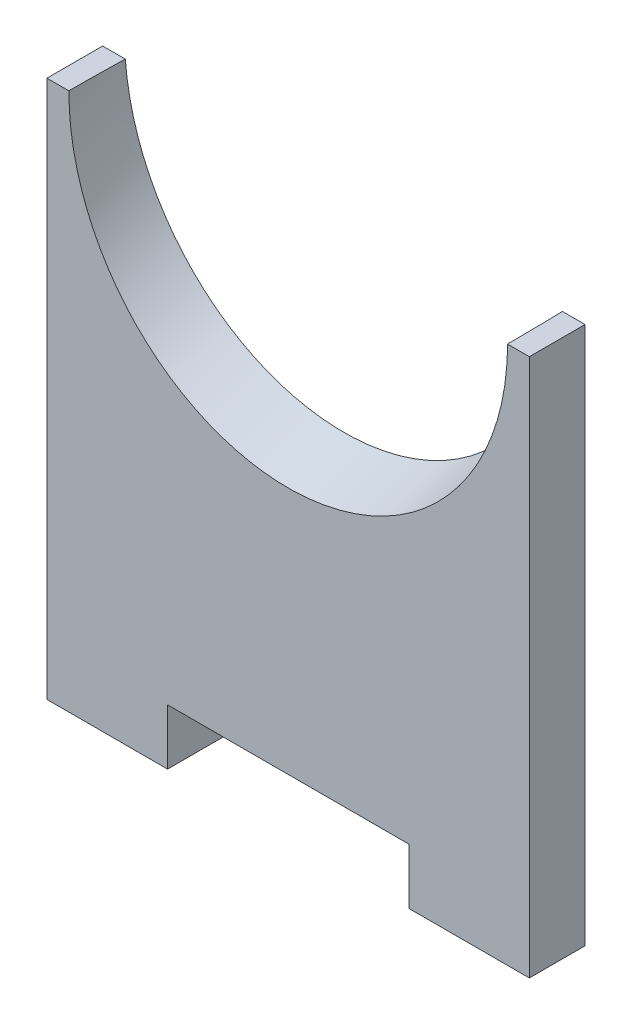
SolidWorks part; units mm, degrees
ref_plane "Front Plane" through (0, 0, 0) normal (0, 0, 1) x (1, 0, 0)
ref_plane "Top Plane" through (0, 0, 0) normal (0, 1, 0) x (1, 0, 0)
ref_plane "Right Plane" through (0, 0, 0) normal (1, 0, 0) x (0, 0, -1)
sketch "Sketch2" plane through (0, 0, 0) normal (0, 0, 1) x (1, 0, 0)
  line L0 (27.5, 55) -> (27.5, 29.1207) construction
  line L1 (13.75, 0) -> (41.25, 0)
  line L2 (0, 0) -> (0, 55)
  line L3 (0, 55) -> (55, 55)
  line L4 (55, 0) -> (55, 55)
  line L6 (0, 0) -> (0, -6.35)
  line L7 (0, -6.35) -> (13.75, -6.35)
  line L8 (13.75, 0) -> (13.75, -6.35)
  line L9 (55, -6.35) -> (41.25, -6.35)
  line L10 (41.25, 0) -> (41.25, -6.35)
  line L12 (55, 0) -> (55, -6.35)
  dimension "D1" = 55
  dimension "D2" = 55
  dimension "D3" = 13.75
  dimension "D4" = 6.35
  dimension "D5" = 6.35
extrude "Boss-Extrude1" add sketch "Sketch2" along normal blind 6.35
ref_plane "Plane1" through (27.5, 0, 0) normal (1, 0, 0) x (0, 0, -1)
sketch "Sketch5" plane through (27.5, 0, 0) normal (1, 0, 0) x (0, 0, -1)
  line L0 (-6.35, 50) -> (-0.2019, 50) construction
  line L1 (-6.35, 50) -> (0, 52.3112)
  line L2 (-6.35, -6.35) -> (-6.35, 55) construction
  line L3 (0, -6.35) -> (0, 55) construction
  dimension "D1" = 50
  dimension "D2" = 20
sketch "Sketch8" plane through (27.5, 0, 0) normal (1, 0, 0) x (0, 0, -1)
  line L0 (0, 57.2032) -> (-6.35, 54.892) construction
  line L1 (0, 55) -> (0, -6.35) construction
  line L2 (-6.35, 55) -> (-6.35, -6.35) construction
  line L3 (-6.35, 54.892) -> (4.3745, 54.892) construction
  line L4 (-6.35, 54.892) -> (-1.6436, 41.9611) construction
  line L5 (-6.35, 54.892) -> (-9.6815, 64.0451) construction
  dimension "D2" = 20
  dimension "D1" = 54.892
  dimension "D4" = 90
  dimension "D3" = 90
sketch "Sketch9" plane through (0, 0, 0) normal (-1, 0, 0) x (0, 0, 1)
  line L0 (6.35, 54.892) -> (0, 57.2032) construction
  line L1 (6.35, 54.892) -> (0, 54.892) construction
  line L2 (6.35, 54.892) -> (-4.3745, 54.892) construction
  line L3 (0, 55) -> (0, -6.35) construction
  line L4 (6.35, 54.892) -> (0, 37.4455) construction
  line L5 (6.35, 54.892) -> (1.6436, 41.9611) construction
  line L6 (6.35, 54.892) -> (5.4251, 52.3508) construction
  line L7 (6.35, 54.892) -> (9.6815, 64.0451) construction
ref_plane "Plane3" through (0, 4.3803, -12.0348) normal (0, -0.342, 0.9397) x (1, 0, 0)
sketch "Sketch10" plane through (0, 4.3803, -12.0348) normal (0, -0.342, 0.9397) x (1, 0, 0)
  circle A0 centre (27.5, 53.7534) radius 25
  dimension "D1" = 50
extrude "Cut-Extrude1" cut sketch "Sketch10" against normal through all both and the other way through all
equation "\"Wheel Thickness\"= 1in"
equation "\"Wheel Diameter\"= 3in"
equation "\"Motor Rear Diameter\" = 36.2mm"
equation "\"Motor Front Diameter\" = 12mm"
equation "\"Material Thickness\" = .25in"
equation "\"Wheel Cutout Diameter\"= 2cm"
equation "\"Motor Mount Tab Thickness\" = 100mm"
equation "\"Motor Mount Tab Height\" = 40mm"
equation "\"Motor Shaft Diameter\" = 3mm"
equation "\"Wheel Radius Clearance\" = 5mm"
equation "\"Wheel Cutout Width\" = 1.5in"
equation "\"Base Diameter\" = 10in"
equation "\"Wheel Mount Distance\" = 5mm"
equation "\"Motor Mount Distance\" = 50mm"
equation "\"Motor Cutout Length\" = 6in"
equation "\"Motor Cutout Height\" = 2in "
equation "\"Rod Diameter\" = 3/8in"
equation "\"Rod Length\" = 1.5in"
equation "\"Barrel Front Length\" = 1.8in"
equation "\"Barrerl Rear Length\" = 5in "
equation "\"Barrel Fillet Radius\" = 1in "
equation "\"Barrel Angle\" = 20deg"
equation "\"Barrel Diameter\" = 50mm"
equation "\"Barrel Shell Width\" = 2mm"
equation "\"Second Level Diameter\" = 10in"
equation "\"Ball Diameter\" = 40mm"
equation "\"Third Level Length\" = 9in"
equation "\"Third Level Height\" = 9in"
equation "\"Barrel Tab Clearance\" = 5mm"
equation "\"Barrel Tab Distance Away\" = 2mm"
equation "\"Hole Distance Apart\" = 2.8in"
equation "\"Barrel Tab Distance\"= 1.5in "
equation "\"D1@Sketch2\"=\"Barrel Diameter\"+\"Barrel Tab Clearance\""
equation "\"D3@Sketch2\"=(\"Barrel Diameter\"+\"Barrel Tab Clearance\")/4"
equation "\"D4@Sketch2\"=\"Material Thickness\""
equation "\"D2@Sketch2\"=\"Barrel Diameter\"+\"Barrel Tab Clearance\""
equation "\"D5@Sketch2\"=\"Material Thickness\""
equation "\"D1@Boss-Extrude1\"=\"Material Thickness\""
equation "\"D1@Sketch5\"=\"Barrel Diameter\""
equation "\"D2@Sketch5\"=\"Barrel Angle\""
equation "\"D2@Sketch8\"=\"Barrel Angle\""
equation "\"D1@Sketch10\"=\"Barrel Diameter\""
equation "\"D1@Sketch8\"=(\"Barrel Diameter\"/2)+.98in+5mm"
